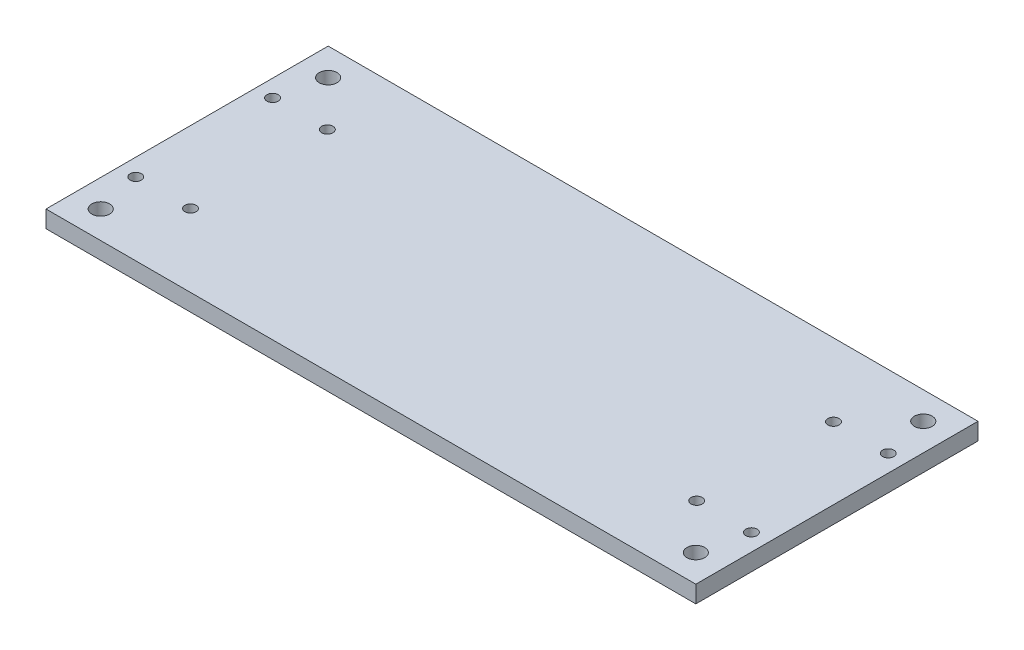
SolidWorks part; units mm, degrees
ref_plane "前视基准面" through (0, 0, 0) normal (0, 0, 1) x (1, 0, 0)
ref_plane "上视基准面" through (0, 0, 0) normal (0, 1, 0) x (1, 0, 0)
ref_plane "右视基准面" through (0, 0, 0) normal (1, 0, 0) x (0, 0, -1)
other "Configuration Table"
ref_plane "基准面1" through (0, 5, 0) normal (0, 1, 0) x (1, 0, 0)
sketch "草图1" plane through (0, 5, 0) normal (0, 1, 0) x (1, 0, 0)
  line L0 (173.75, -82.5) -> (173.75, 82.5)
  line L1 (173.75, 82.5) -> (-173.75, 82.5)
  line L2 (-173.75, 82.5) -> (-173.75, -82.5)
  line L3 (-173.75, -82.5) -> (173.75, -82.5)
  circle A0 centre (-163.75, -70.5) radius 2.6
  circle A1 centre (-163.75, -60.5) radius 2.6
  circle A2 centre (163.75, -60.5) radius 2.6
  circle A3 centre (163.75, -70.5) radius 2.6
extrude "凸台-拉伸1" add sketch "草图1" against normal blind 5
sketch "草图2" plane through (0, 5, 0) normal (0, 1, 0) x (1, 0, 0)
  line L0 (173.75, -55.3346) -> (-173.75, -55.3346)
  line L1 (0, 82.5) -> (0, -82.5) construction
  line L2 (-16.25, 82.5) -> (-16.25, -82.5)
  line L3 (-173.75, 0) -> (173.75, 0)
  line L4 (-173.75, -82.5) -> (173.75, -82.5)
  line L5 (173.75, -82.5) -> (173.75, 82.5)
  line L6 (173.75, 82.5) -> (-173.75, 82.5)
  line L7 (-173.75, 82.5) -> (-173.75, -82.5)
  line L8 (-173.75, -82.5) -> (173.75, -82.5)
  line L9 (173.75, -82.5) -> (173.75, 82.5)
  line L10 (173.75, 82.5) -> (-173.75, 82.5)
  line L11 (-173.75, 82.5) -> (-173.75, -82.5)
  circle M6 centre (163.75, -70.5) radius 2.6
  circle M7 centre (163.75, -60.5) radius 2.6
  circle M8 centre (-163.75, -60.5) radius 2.6
  circle M9 centre (-163.75, -70.5) radius 2.6
  line M10 (-173.75, -82.5) -> (173.75, -82.5)
  line M11 (173.75, -82.5) -> (173.75, 82.5)
  line M12 (173.75, 82.5) -> (-173.75, 82.5)
  line M13 (-173.75, 82.5) -> (-173.75, -82.5)
  dimension "D2" = 190
  dimension "D1" = 0
extrude "切除-拉伸2" cut sketch "草图2" against normal blind 5 contours L3 L2 M13 M12 | L3 L0 L2 M13 | L2 L0 M13 M10 M9 M8 | L0 L1 L8 M11 M6 M7 | L1 L0 L2 M10 | L1 L3 L2 L0 | L3 L1 L0 M11
sketch "草图4" plane through (0, 5, 0) normal (0, 1, 0) x (1, 0, 0)
  line L0 (-16.25, 41.25) -> (173.75, 41.25) construction
  line L1 (78.75, 82.5) -> (78.75, 0) construction
  line L4 (173.75, 82.5) -> (-16.25, 82.5)
  line L5 (-16.25, 82.5) -> (-16.25, 0)
  line L6 (-16.25, 0) -> (173.75, 0)
  line L7 (173.75, 0) -> (173.75, 82.5)
  line L8 (173.75, 82.5) -> (-16.25, 82.5)
  line L9 (-16.25, 82.5) -> (-16.25, 0)
  line L10 (-16.25, 0) -> (173.75, 0)
  line L11 (173.75, 0) -> (173.75, 82.5)
  circle A2 centre (-8.25, 74.5) radius 2.6
  circle A4 centre (-8.25, 8) radius 2.6
  circle A5 centre (165.75, 8) radius 2.6
  circle A6 centre (165.75, 74.5) radius 2.6
  dimension "D2" = 5.2
  dimension "D3" = 8
  dimension "D4" = 8
  dimension "D1" = 0
extrude "切除-拉伸3" cut sketch "草图4" against normal blind 5 contours A6 | A5 | A2 | A4
sketch "草图5" plane through (0, 0, 0) normal (0, -1, 0) x (1, 0, 0)
  circle A0 centre (4.75, -61.25) radius 1.65
  circle A1 centre (-11.25, -61.25) radius 1.65
  circle A2 centre (-11.25, -21.25) radius 1.65
  circle A3 centre (4.75, -21.25) radius 1.65
  circle A4 centre (168.75, -61.25) radius 1.65
  circle A5 centre (152.75, -61.25) radius 1.65
  circle A6 centre (168.75, -21.25) radius 1.65
  circle A7 centre (152.75, -21.25) radius 1.65
  point P24 (0, 0)
  point P25 (0, 0)
extrude "切除-拉伸4" cut sketch "草图5" against normal blind 10 contours A1 | A0 | A3 | A5 | A4 | A7 | A6 | A2
